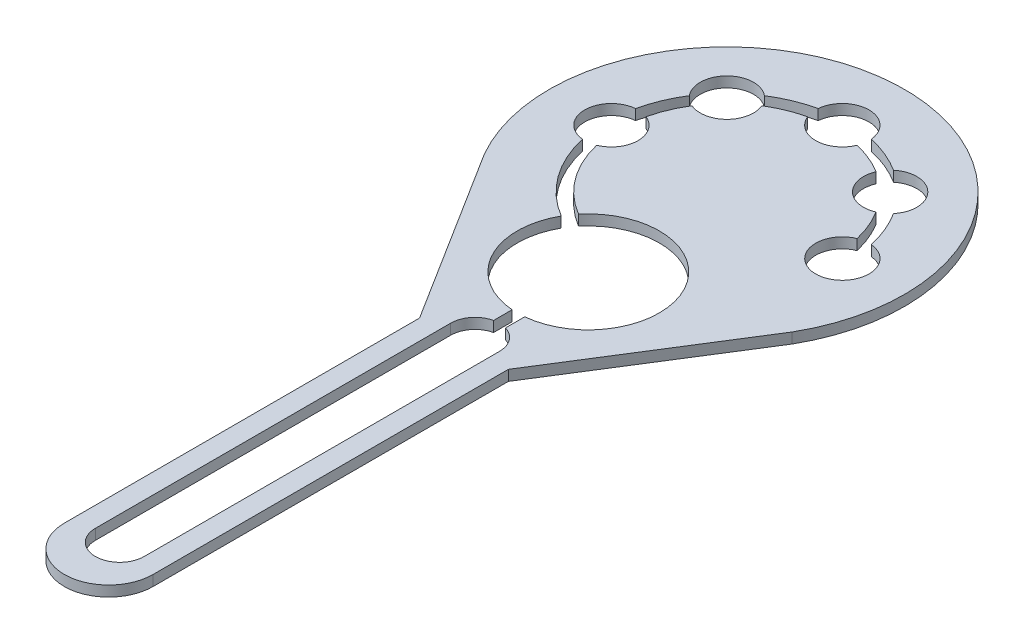
SolidWorks part; units mm, degrees
ref_plane "Front Plane" through (0, 0, 0) normal (0, 0, 1) x (1, 0, 0)
ref_plane "Top Plane" through (0, 0, 0) normal (0, 1, 0) x (1, 0, 0)
ref_plane "Right Plane" through (0, 0, 0) normal (1, 0, 0) x (0, 0, -1)
sketch "Sketch1" plane through (0, 0, 0) normal (0, 1, 0) x (1, 0, 0)
  line L0 (0, -75.184) -> (0, -176.784) construction
  line L1 (12.7, -75.184) -> (12.7, -176.784)
  line L2 (-12.7, -75.184) -> (-12.7, -176.784)
  line L3 (-44.0264, -25.344) -> (-12.7, -75.184)
  line L4 (44.0264, -25.344) -> (12.7, -75.184)
  arc A0 (44.0264, -25.344) -> (-44.0264, -25.344) centre (0, 0) ccw
  circle A1 centre (0, 0) radius 33.02
  arc A2 (12.7, -75.184) -> (-12.7, -75.184) centre (0, -75.184) ccw
  arc A3 (-12.7, -176.784) -> (12.7, -176.784) centre (0, -176.784) ccw
  circle A4 centre (0, -39.624) radius 19.05
  point P7 (0, -125.984)
  point P14 (0, 0)
  point P15 (0, 0)
  dimension "D1" = 50.8
  dimension "D2" = 66.04
  dimension "D6" = 38.1
  dimension "D3" = 101.6
  dimension "D4" = 75.184
  dimension "D5" = 35.56
  dimension "D7" = 25.4
extrude "Boss-Extrude1" add sketch "Sketch1" along normal blind 2.9972
sketch "Sketch2" plane through (0, 2.9972, 0) normal (0, 1, 0) x (1, 0, 0)
  circle A0 centre (-33.02, 0) radius 7.62
  circle A1 centre (-23.3487, 23.3487) radius 7.62
  circle A2 centre (0, 33.02) radius 7.62
  circle A3 centre (23.3487, 23.3487) radius 7.62
  circle A4 centre (33.02, 0) radius 7.62
  point P14 (0, 0)
  dimension "D1" = 15.24
  dimension "D2" = 33.02
  dimension "D3" = 5
extrude "Cut-Extrude1" cut sketch "Sketch2" against normal through all
sketch "Sketch3" plane through (0, 2.9972, 0) normal (0, 1, 0) x (1, 0, 0)
  line L0 (-15.3169, -30.9625) -> (-1.2558, -30.9625)
  line L1 (30.988, 0) -> (34.544, 0)
  arc A0 (-15.3169, -30.9625) -> (34.544, 0) centre (0, 0) cw
  arc A1 (-1.2558, -30.9625) -> (30.988, 0) centre (0, 0) cw
  point P6 (-20.5741, -26.0619)
  point P7 (-14.6782, -27.2911)
  point P8 (-16.856, -26.0025)
  point P9 (-18.5577, -28.5144)
  point P10 (30.982, -0.6118)
  point P11 (-15.3169, -30.9625)
  dimension "D2" = 30.988
  dimension "D1" = 34.544
extrude "Cut-Extrude2" cut sketch "Sketch3" against normal through all
sketch "Sketch4" plane through (0, 2.9972, 0) normal (0, 1, 0) x (1, 0, 0)
  circle A0 centre (0, -39.624) radius 20.32
  dimension "D1" = 40.64
  dimension "D2" = 39.624
extrude "Cut-Extrude3" cut sketch "Sketch4" against normal through all
sketch "Sketch5" plane through (0, 2.9972, 0) normal (0, 1, 0) x (1, 0, 0)
  line L0 (0, -72.009) -> (0, -173.609) construction
  line L1 (6.985, -72.009) -> (6.985, -173.609)
  line L2 (-6.985, -72.009) -> (-6.985, -173.609)
  arc A0 (6.985, -72.009) -> (-6.985, -72.009) centre (0, -72.009) ccw
  arc A1 (-6.985, -173.609) -> (6.985, -173.609) centre (0, -173.609) ccw
  arc A2 (-17.709, -29.6594) -> (-15.6958, -26.7188) centre (0, -39.624) ccw construction
  point P3 (0, -122.809)
  dimension "D3" = 32.385
  dimension "D1" = 101.6
  dimension "D2" = 13.97
extrude "Cut-Extrude4" cut sketch "Sketch5" against normal through all
sketch "Sketch6" plane through (0, 2.9972, 0) normal (0, 1, 0) x (1, 0, 0)
  line L1 (-1.524, -57.56) -> (2.032, -57.56)
  line L2 (-1.524, -57.56) -> (-1.524, -67.3117)
  line L3 (-1.524, -67.3117) -> (2.032, -67.3117)
  line L4 (2.032, -57.56) -> (2.032, -67.3117)
  line L5 (-1.524, -57.56) -> (2.032, -67.3117) construction
  line L6 (-1.524, -67.3117) -> (2.032, -57.56) construction
  point P0 (0.254, -62.4359)
  point P5 (0, -62.4359)
  dimension "D1" = 3.556
extrude "Cut-Extrude5" cut sketch "Sketch6" against normal through all
